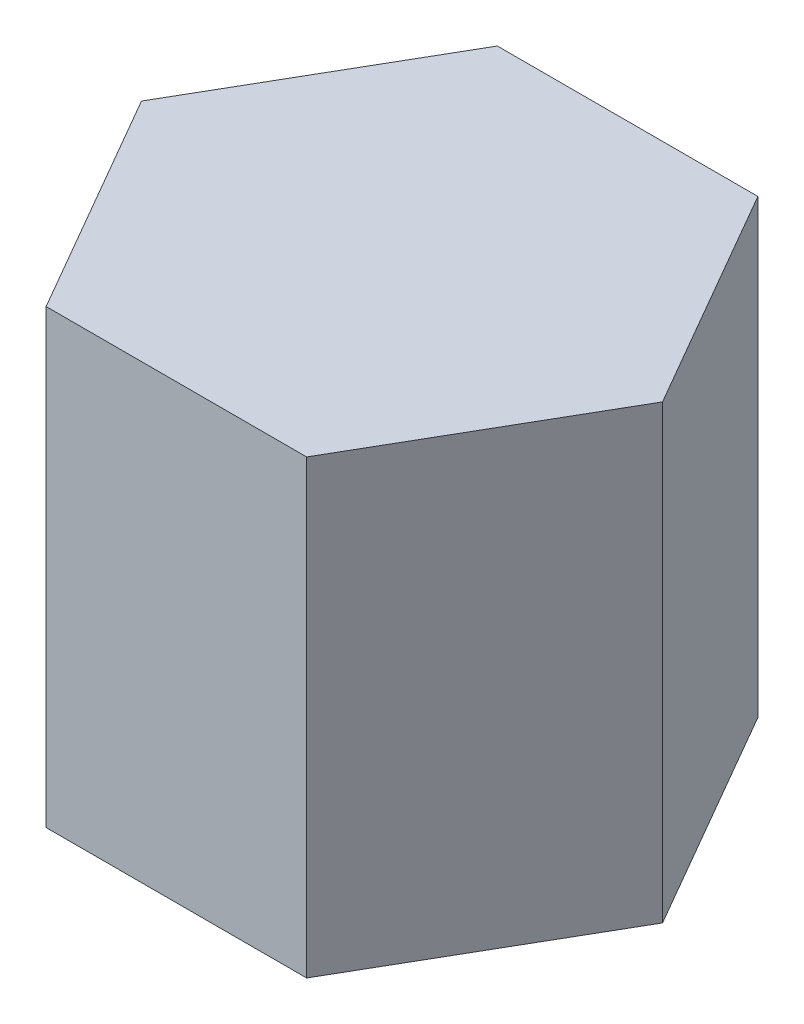
SolidWorks part; units mm, degrees
material "보통 탄소강"
ref_plane "Front" through (0, 0, 0) normal (0, 0, 1) x (1, 0, 0)
ref_plane "Top" through (0, 0, 0) normal (0, 1, 0) x (1, 0, 0)
ref_plane "Right" through (0, 0, 0) normal (1, 0, 0) x (0, 0, -1)
sketch "Sketch1" plane through (0, 0, 0) normal (0, 1, 0) x (1, 0, 0)
  line L1 (-28.8675, 50) -> (-57.735, 0)
  line L2 (-57.735, 0) -> (-28.8675, -50)
  line L3 (-28.8675, -50) -> (28.8675, -50)
  line L4 (28.8675, -50) -> (57.735, 0)
  line L5 (57.735, 0) -> (28.8675, 50)
  line L6 (28.8675, 50) -> (-28.8675, 50)
  circle A0 centre (0, 0) radius 50 construction
  dimension "D1" = 100
extrude "Extrude1" add sketch "Sketch1" along normal blind 100
equation "\"D\" = 100mm"
equation "\"H\" = 100mm"
equation "\"D1@Sketch1\"= \"D\""
equation "\"D1@Extrude1\"= \"H\""
